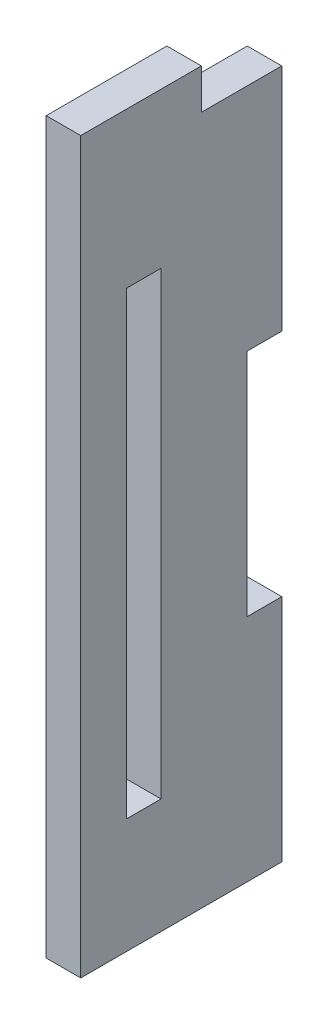
SolidWorks part; units mm, degrees
ref_plane "Alzado" through (0, 0, 0) normal (0, 0, 1) x (1, 0, 0)
ref_plane "Planta" through (0, 0, 0) normal (0, 1, 0) x (1, 0, 0)
ref_plane "Vista lateral" through (0, 0, 0) normal (1, 0, 0) x (0, 0, -1)
sketch "Croquis1" plane through (0, 0, 0) normal (1, 0, 0) x (0, 0, -1)
  line L1 (0, 0) -> (35, 0)
  line L2 (0, 0) -> (0, 120)
  line L3 (0, 120) -> (35, 120)
  line L4 (35, 0) -> (35, 120)
  dimension "D1" = 120
  dimension "D2" = 35
extrude "Saliente-Extruir1" add sketch "Croquis1" along normal blind 6
sketch "Croquis3" plane through (0, 0, 0) normal (1, 0, 0) x (0, 0, -1)
  line L0 (35, 0) -> (35, 120) construction
  line L1 (35, 39.99) -> (28.98, 39.99)
  line L2 (35, 39.99) -> (35, 80.01)
  line L3 (35, 80.01) -> (28.98, 80.01)
  line L4 (28.98, 39.99) -> (28.98, 80.01)
  line L5 (0, 120) -> (0, 0) construction
  point P6 (0, 60)
  point P9 (28.98, 60)
  dimension "D1" = 6.02
  dimension "D2" = 40.02
extrude "Cortar-Extruir1" cut sketch "Croquis3" along normal through all
sketch "Croquis4" plane through (0, 0, 0) normal (1, 0, 0) x (0, 0, -1)
  line L0 (0, 120) -> (0, 0) construction
  line L1 (7.93, 100) -> (13.98, 100)
  line L2 (7.93, 100) -> (7.93, 20)
  line L3 (7.93, 20) -> (13.98, 20)
  line L4 (13.98, 100) -> (13.98, 20)
  line L5 (28.98, 80.01) -> (28.98, 39.99) construction
  point P4 (7.93, 60)
  point P7 (0, 60)
  dimension "D1" = 80
  dimension "D2" = 15
  dimension "D3" = 6.05
extrude "Cortar-Extruir2" cut sketch "Croquis4" along normal blind 10
sketch "Croquis5" plane through (0, 0, 0) normal (1, 0, 0) x (0, 0, -1)
  line L1 (0, 120) -> (21, 120)
  line L2 (0, 120) -> (0, 127)
  line L3 (0, 127) -> (21, 127)
  line L4 (21, 120) -> (21, 127)
  line L7 (35, 80.01) -> (35, 120) construction
  dimension "D1" = 7
  dimension "D2" = 14
extrude "Saliente-Extruir2" add sketch "Croquis5" along normal blind 6
